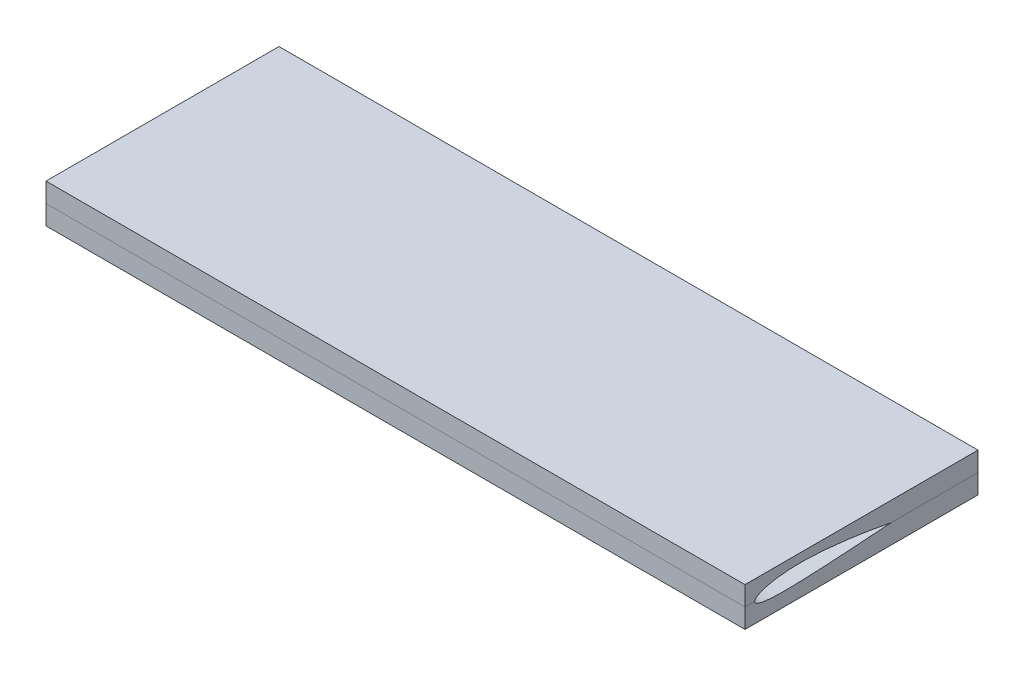
SolidWorks part; units mm, degrees
ref_plane "Front Plane" through (0, 0, 0) normal (0, 0, 1) x (1, 0, 0)
ref_plane "Top Plane" through (0, 0, 0) normal (0, 1, 0) x (1, 0, 0)
ref_plane "Right Plane" through (0, 0, 0) normal (1, 0, 0) x (0, 0, -1)
curve "Curve1"
  spline degree 3 poles (0, 25.4, 0.0064) (0, 25.2657, 0.0346) (0, 24.9974, 0.0911) (0, 24.5944, 0.1721) (0, 24.1917, 0.2509) (0, 23.7893, 0.3278) (0, 23.3874, 0.4029) (0, 22.9859, 0.4765) (0, 22.5851, 0.5485) (0, 22.1849, 0.619) (0, 21.7856, 0.688) (0, 21.3872, 0.7554) (0, 20.9898, 0.8212) (0, 20.5935, 0.8853) (0, 20.1985, 0.9476) (0, 19.8047, 1.0082) (0, 19.4123, 1.067) (0, 19.0215, 1.124) (0, 18.6322, 1.1792) (0, 18.2447, 1.2326) (0, 17.859, 1.2841) (0, 17.4751, 1.3339) (0, 17.0933, 1.382) (0, 16.7135, 1.4283) (0, 16.3359, 1.4729) (0, 15.9606, 1.5158) (0, 15.5877, 1.5571) (0, 15.2173, 1.5967) (0, 14.8494, 1.6346) (0, 14.4842, 1.6709) (0, 14.1217, 1.7054) (0, 13.7621, 1.7383) (0, 13.4054, 1.7695) (0, 13.0517, 1.7989) (0, 12.7011, 1.8265) (0, 12.3537, 1.8522) (0, 12.0097, 1.8761) (0, 11.6689, 1.8981) (0, 11.3317, 1.918) (0, 10.9979, 1.936) (0, 10.6678, 1.9519) (0, 10.3414, 1.9657) (0, 10.0188, 1.9774) (0, 9.7001, 1.9869) (0, 9.3853, 1.9942) (0, 9.0746, 1.9993) (0, 8.7679, 2.0022) (0, 8.4655, 2.0029) (0, 8.1673, 2.0014) (0, 7.8734, 1.9977) (0, 7.584, 1.9918) (0, 7.2991, 1.9837) (0, 7.0187, 1.9735) (0, 6.7429, 1.9612) (0, 6.4718, 1.9468) (0, 6.2055, 1.9304) (0, 5.944, 1.912) (0, 5.6874, 1.8917) (0, 5.4358, 1.8694) (0, 5.1892, 1.8454) (0, 4.9477, 1.8195) (0, 4.7114, 1.792) (0, 4.4802, 1.7628) (0, 4.2543, 1.7319) (0, 4.0338, 1.6995) (0, 3.8186, 1.6656) (0, 3.6089, 1.6303) (0, 3.4046, 1.5936) (0, 3.2059, 1.5556) (0, 3.0127, 1.5163) (0, 2.8252, 1.4759) (0, 2.6434, 1.4343) (0, 2.4673, 1.3917) (0, 2.297, 1.3481) (0, 2.1325, 1.3035) (0, 1.9738, 1.2581) (0, 1.8211, 1.2119) (0, 1.6742, 1.1649) (0, 1.5334, 1.1173) (0, 1.3985, 1.0691) (0, 1.2697, 1.0204) (0, 1.147, 0.9712) (0, 1.0304, 0.9215) (0, 0.9199, 0.8715) (0, 0.8155, 0.8212) (0, 0.7173, 0.7706) (0, 0.6254, 0.7198) (0, 0.5396, 0.6689) (0, 0.4601, 0.6178) (0, 0.3869, 0.5666) (0, 0.3199, 0.5153) (0, 0.2592, 0.4639) (0, 0.2049, 0.4126) (0, 0.1568, 0.3611) (0, 0.1151, 0.3097) (0, 0.0797, 0.2582) (0, 0.0507, 0.2067) (0, 0.0281, 0.1551) (0, 0.0119, 0.1034) (0, 0.0022, 0.0517) (0, -0.0011, 0.0014) (0, 0.0021, -0.0476) (0, 0.0119, -0.095) (0, 0.0281, -0.1421) (0, 0.0507, -0.1886) (0, 0.0797, -0.2345) (0, 0.1151, -0.2796) (0, 0.1568, -0.3238) (0, 0.2049, -0.3671) (0, 0.2593, -0.4092) (0, 0.32, -0.4502) (0, 0.387, -0.49) (0, 0.4602, -0.5285) (0, 0.5397, -0.5656) (0, 0.6255, -0.6013) (0, 0.7175, -0.6357) (0, 0.8157, -0.6686) (0, 0.92, -0.7001) (0, 1.0306, -0.7301) (0, 1.1472, -0.7588) (0, 1.2699, -0.786) (0, 1.3988, -0.8119) (0, 1.5336, -0.8364) (0, 1.6745, -0.8596) (0, 1.8213, -0.8815) (0, 1.974, -0.9021) (0, 2.1327, -0.9215) (0, 2.2972, -0.9397) (0, 2.4675, -0.9567) (0, 2.6436, -0.9725) (0, 2.8254, -0.9871) (0, 3.0129, -1.0006) (0, 3.206, -1.0129) (0, 3.4048, -1.0241) (0, 3.609, -1.0341) (0, 3.8188, -1.043) (0, 4.0339, -1.0507) (0, 4.2545, -1.0573) (0, 4.4804, -1.0628) (0, 4.7115, -1.0671) (0, 4.9478, -1.0703) (0, 5.1893, -1.0723) (0, 5.4359, -1.0732) (0, 5.6875, -1.073) (0, 5.9441, -1.0718) (0, 6.2056, -1.0694) (0, 6.4719, -1.0661) (0, 6.7429, -1.0617) (0, 7.0187, -1.0564) (0, 7.2991, -1.0502) (0, 7.584, -1.0431) (0, 7.8735, -1.0352) (0, 8.1673, -1.0265) (0, 8.4655, -1.017) (0, 8.7679, -1.0069) (0, 9.0746, -0.996) (0, 9.3853, -0.9846) (0, 9.7001, -0.9725) (0, 10.0188, -0.9599) (0, 10.3414, -0.9466) (0, 10.6678, -0.9328) (0, 10.9979, -0.9185) (0, 11.3316, -0.9035) (0, 11.6689, -0.888) (0, 12.0096, -0.8718) (0, 12.3537, -0.855) (0, 12.7011, -0.8375) (0, 13.0517, -0.8194) (0, 13.4053, -0.8005) (0, 13.762, -0.781) (0, 14.1217, -0.7608) (0, 14.4841, -0.7398) (0, 14.8494, -0.7181) (0, 15.2172, -0.6958) (0, 15.5877, -0.6729) (0, 15.9606, -0.6493) (0, 16.3359, -0.6253) (0, 16.7134, -0.6007) (0, 17.0932, -0.5758) (0, 17.475, -0.5506) (0, 17.8589, -0.5252) (0, 18.2446, -0.4996) (0, 18.6321, -0.4739) (0, 19.0214, -0.4481) (0, 19.4122, -0.4224) (0, 19.8046, -0.3966) (0, 20.1983, -0.3708) (0, 20.5934, -0.3449) (0, 20.9897, -0.3189) (0, 21.3871, -0.2926) (0, 21.7855, -0.2659) (0, 22.1848, -0.2386) (0, 22.585, -0.2108) (0, 22.9858, -0.1822) (0, 23.3872, -0.153) (0, 23.7892, -0.1231) (0, 24.1915, -0.0928) (0, 24.5941, -0.0626) (0, 24.997, -0.0331) (0, 25.2657, -0.0153) (0, 25.4, -0.0064) knots 0 0 0 0 0.007941 0.015868 0.023782 0.031684 0.039571 0.047444 0.055299 0.063136 0.070953 0.078747 0.086517 0.09426 0.101975 0.10966 0.117312 0.124931 0.132515 0.14006 0.147567 0.155033 0.162457 0.169836 0.17717 0.184456 0.191693 0.198879 0.206013 0.213092 0.220115 0.227081 0.233988 0.240834 0.247617 0.254336 0.260989 0.267575 0.274092 0.280538 0.286913 0.293214 0.299441 0.305592 0.311665 0.31766 0.323575 0.329409 0.33516 0.340829 0.346413 0.351912 0.357324 0.362648 0.367884 0.373031 0.378086 0.383051 0.387923 0.392702 0.397387 0.401977 0.406471 0.410868 0.415168 0.41937 0.423472 0.427475 0.431378 0.435179 0.438879 0.442477 0.445971 0.449362 0.45265 0.455833 0.458911 0.461884 0.464751 0.467513 0.470169 0.47272 0.475165 0.477504 0.479738 0.481867 0.483893 0.485816 0.487638 0.48936 0.490986 0.492517 0.493957 0.495311 0.496586 0.497786 0.498922 0.500002 0.50104 0.502047 0.503039 0.503952 0.504878 0.505831 0.506824 0.507866 0.508967 0.510136 0.51138 0.512704 0.514115 0.515615 0.517209 0.518901 0.520691 0.522584 0.524581 0.526682 0.528891 0.531207 0.533632 0.536166 0.538809 0.541562 0.544425 0.547398 0.550481 0.553673 0.556974 0.560384 0.563903 0.567529 0.571261 0.5751 0.579045 0.583094 0.587247 0.591503 0.595862 0.600321 0.60488 0.609539 0.614295 0.619148 0.624097 0.629141 0.634278 0.639507 0.644828 0.650237 0.655735 0.66132 0.666991 0.672745 0.678583 0.684501 0.690499 0.696575 0.702728 0.708956 0.715257 0.72163 0.728074 0.734587 0.741166 0.747811 0.75452 0.761292 0.768124 0.775014 0.781962 0.788966 0.796023 0.803132 0.810291 0.817498 0.824752 0.832051 0.839391 0.846773 0.854193 0.86165 0.869142 0.876666 0.884222 0.891806 0.899418 0.907055 0.914715 0.922398 0.9301 0.93782 0.945557 0.953308 0.961072 0.968847 0.97663 0.984418 0.99221 1 1 1 1
sketch "Sketch1" plane through (0, 0, 0) normal (1, 0, 0) x (0, 0, -1)
  line L0 (0, -18.8425) -> (0, 18.8425) construction
  line L1 (0, 0) -> (355.6, 0) construction
  line L2 (355.6, 0.0889) -> (355.6, -0.0889)
  line L3 (-25.4, 0) -> (584.2, 0) construction
  line L4 (-25.4, 50.8) -> (584.2, 50.8)
  line L5 (-25.4, 50.8) -> (-25.4, -50.8)
  line L6 (-25.4, -50.8) -> (584.2, -50.8)
  line L7 (584.2, 50.8) -> (584.2, -50.8)
  spline S1 degree 3 poles (355.6, 0.0889) (353.7199, 0.4845) (349.9629, 1.275) (344.3214, 2.4083) (338.6837, 3.5122) (333.0502, 4.5878) (327.4227, 5.6394) (321.8023, 6.6689) (314.3291, 8.0114) (303.1704, 9.9584) (290.1943, 12.1074) (277.2898, 14.1187) (266.3272, 15.7392) (251.9073, 17.7534) (237.6208, 19.5782) (223.4846, 21.2212) (213.08, 22.3524) (202.819, 23.3908) (192.7118, 24.3352) (182.7688, 25.1832) (172.9997, 25.9306) (161.8755, 26.676) (149.4917, 27.3461) (135.9508, 27.8404) (122.9069, 28.0599) (110.3896, 28.0006) (99.6722, 27.701) (90.668, 27.2623) (83.28, 26.7759) (76.1662, 26.1811) (69.3337, 25.4837) (62.7894, 24.6897) (56.5399, 23.8056) (50.5914, 22.8379) (44.95, 21.7935) (39.6211, 20.6793) (35.3846, 19.6843) (31.4108, 18.6663) (28.394, 17.8281) (25.4942, 16.9508) (23.4387, 16.2935) (21.4668, 15.6269) (19.579, 14.9519) (17.7757, 14.2694) (16.0574, 13.5801) (14.4245, 12.885) (12.8774, 12.1848) (11.4165, 11.4803) (10.0421, 10.7721) (8.7545, 10.061) (7.5541, 9.3474) (6.4411, 8.632) (5.4158, 7.9151) (4.4783, 7.1971) (3.629, 6.4783) (2.8679, 5.759) (2.1952, 5.0392) (1.6111, 4.3188) (1.1159, 3.598) (0.7098, 2.8765) (0.3933, 2.1542) (0.1665, 1.4311) (0.0307, 0.7073) (-0.0151, 0.0023) (0.0301, -0.6832) (0.1668, -1.347) (0.3933, -2.0057) (0.71, -2.6573) (1.1162, -3.2998) (1.6116, -3.9314) (2.1959, -4.5505) (2.8689, -5.1559) (3.6303, -5.7461) (4.48, -6.32) (5.4178, -6.8766) (6.4434, -7.4151) (7.5567, -7.9348) (8.7575, -8.4352) (10.0453, -8.9158) (11.4199, -9.3765) (12.8811, -9.8173) (14.4283, -10.238) (16.0614, -10.639) (17.7798, -11.0204) (19.5832, -11.3825) (21.4711, -11.7257) (23.4431, -12.0503) (25.4986, -12.3568) (27.6372, -12.6455) (29.8583, -12.9169) (32.1613, -13.1711) (35.3929, -13.493) (39.6335, -13.8511) (44.9617, -14.2099) (50.6024, -14.5049) (56.5502, -14.736) (62.7989, -14.9032) (69.3424, -15.0064) (76.174, -15.0463) (83.287, -15.0243) (90.674, -14.9431) (98.3278, -14.8063) (106.2405, -14.6184) (114.4043, -14.3842) (122.8109, -14.1086) (131.4519, -13.7959) (140.3186, -13.4492) (149.4021, -13.0703) (161.9212, -12.5165) (174.6977, -11.9012) (187.7181, -11.2171) (197.7443, -10.6596) (207.9293, -10.0623) (220.0255, -9.3192) (232.2793, -8.5306) (244.6787, -7.7127) (255.4498, -6.9969) (264.4908, -6.3975) (273.6091, -5.7962) (282.7955, -5.1936) (293.872, -4.4675) (303.1431, -3.8509) (310.5879, -3.3431) (316.1897, -2.953) (321.8014, -2.5531) (327.4215, -2.143) (333.0486, -1.7243) (338.6813, -1.2999) (344.3181, -0.8776) (349.9574, -0.4632) (353.7192, -0.2137) (355.6, -0.0889) knots 0 0 0 0 0.007941 0.015868 0.023782 0.031684 0.039571 0.047444 0.055299 0.070953 0.09426 0.10966 0.124931 0.14006 0.169836 0.184456 0.198879 0.213092 0.227081 0.240834 0.254336 0.267575 0.286913 0.305592 0.323575 0.340829 0.357324 0.367884 0.378086 0.387923 0.397387 0.406471 0.415168 0.423472 0.431378 0.438879 0.445971 0.449362 0.455833 0.458911 0.461884 0.464751 0.467513 0.470169 0.47272 0.475165 0.477504 0.479738 0.481867 0.483893 0.485816 0.487638 0.48936 0.490986 0.492517 0.493957 0.495311 0.496586 0.497786 0.498922 0.500002 0.50104 0.502047 0.503039 0.503952 0.504878 0.505831 0.506824 0.507866 0.508967 0.510136 0.51138 0.512704 0.514115 0.515615 0.517209 0.518901 0.520691 0.522584 0.524581 0.526682 0.528891 0.531207 0.533632 0.536166 0.538809 0.541562 0.544425 0.547398 0.550481 0.553673 0.556974 0.563903 0.571261 0.579045 0.587247 0.595862 0.60488 0.614295 0.624097 0.634278 0.644828 0.655735 0.666991 0.678583 0.690499 0.702728 0.715257 0.728074 0.75452 0.768124 0.781962 0.796023 0.810291 0.832051 0.846773 0.86165 0.876666 0.884222 0.899418 0.914715 0.9301 0.93782 0.945557 0.953308 0.961072 0.968847 0.97663 0.984418 0.99221 1 1 1 1
  point P4 (0, 0)
  point P14 (0, 0)
  dimension "D1" = 355.6
  dimension "D2" = 101.6
  dimension "D3" = 609.6
  dimension "D4" = 25.4
extrude "Boss-Extrude1" add sketch "Sketch1" along normal mid plane 1828.8
split "Split1" trim tools "Top Plane" bodies to split 101 resulting bodies 102 103
